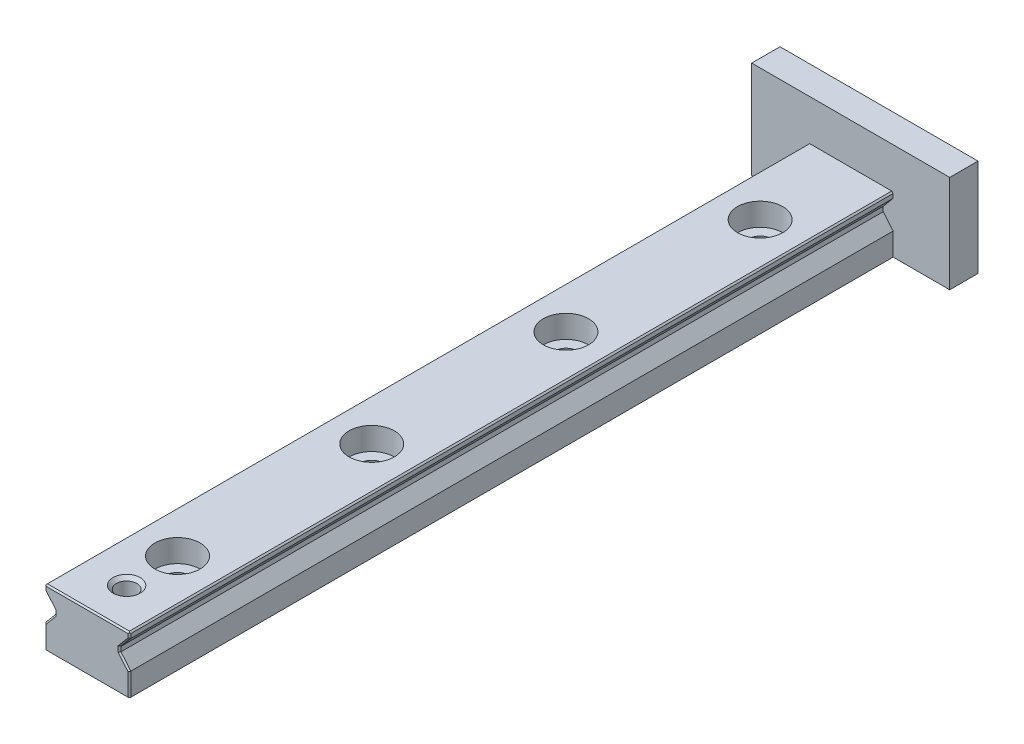
SolidWorks part; units mm, degrees
material "PET"
ref_plane "Přední rovina" through (0, 0, 0) normal (0, 0, 1) x (1, 0, 0)
ref_plane "Horní rovina" through (0, 0, 0) normal (0, 1, 0) x (1, 0, 0)
ref_plane "Pravá rovina" through (0, 0, 0) normal (1, 0, 0) x (0, 0, -1)
sketch "Skica1" plane through (0, 0, 0) normal (0, 0, 1) x (1, 0, 0)
  line L0 (0, 9) -> (1.7495, 6.915)
  line L1 (0, 0) -> (15, 0)
  line L2 (0, 0) -> (0, 4)
  line L3 (0, 10) -> (15, 10)
  line L4 (15, 0) -> (15, 4)
  line L5 (0, 0) -> (15, 10) construction
  line L6 (0, 10) -> (15, 0) construction
  line L7 (1.7495, 6.915) -> (1.7495, 6.085)
  line L8 (1.7495, 6.085) -> (0, 4)
  line L9 (0, 9) -> (0, 10)
  line L10 (7.5, 0) -> (7.5, 10) construction
  line L11 (15, 9) -> (13.2505, 6.915)
  line L12 (13.2505, 6.915) -> (13.2505, 6.085)
  line L13 (13.2505, 6.085) -> (15, 4)
  line L14 (15, 9) -> (15, 10)
  point P4 (7.5, 5)
  dimension "D1" = 10
  dimension "D2" = 15
  dimension "D3" = 4
  dimension "D4" = 5
  dimension "D5" = 0.83
  dimension "D6" = 50
  dimension "D7" = 50
extrude "Přidat vysunutím1" add sketch "Skica1" along normal blind 140
sketch "Skica2" plane through (0, 0, 0) normal (0, 0, -1) x (-1, 0, 0)
  line L1 (-25, 0) -> (10, 0)
  line L2 (-25, 0) -> (-25, 17.21)
  line L3 (-25, 17.21) -> (10, 17.21)
  line L4 (10, 0) -> (10, 17.21)
  line L5 (-25, 0) -> (10, 17.21) construction
  line L6 (-25, 17.21) -> (10, 0) construction
  line L7 (-15, 0) -> (-15, 4) construction
  line L8 (0, 4) -> (0, 0) construction
  point P4 (-7.5, 8.605)
  dimension "D1" = 17.21
  dimension "D2" = 10
  dimension "D3" = 10
extrude "Přidat vysunutím2" add sketch "Skica2" against normal blind 5
sketch "Skica3" plane through (0, 10, 0) normal (0, 1, 0) x (1, 0, 0)
  line L0 (7.5, -5) -> (7.5, -140) construction
  line L1 (15, -5) -> (0, -5) construction
  line L2 (15, -140) -> (0, -140) construction
  line L3 (-10, -5) -> (25, -5) construction
  circle A0 centre (7.5, -124) radius 2.1
  circle A4 centre (7.5, -89.6667) radius 2.1
  circle A5 centre (7.5, -55.3333) radius 2.1
  circle A6 centre (7.5, -21) radius 2.1
  dimension "D1" = 4.2
  dimension "D2" = 16
  dimension "D4" = 16
  dimension "D3" = 4
extrude "Odebrat vysunutím1" cut sketch "Skica3" against normal up to surface (10 mm away) up to face at (7.5, 0, 37.5)
sketch "Skica4" plane through (0, 10, 0) normal (0, 1, 0) x (1, 0, 0)
  circle A0 centre (7.5, -124) radius 4
  circle A3 centre (7.5, -89.67) radius 4
  circle A4 centre (7.5, -55.34) radius 4
  circle A5 centre (7.5, -21.01) radius 4
  dimension "D1" = 8
  dimension "D2" = 4
extrude "Odebrat vysunutím2" cut sketch "Skica4" against normal blind 4
sketch "Skica5" plane through (0, 10, 0) normal (0, 1, 0) x (1, 0, 0)
  line L0 (7.5, -124) -> (7.5, -140) construction
  line L1 (15, -140) -> (0, -140) construction
  circle A0 centre (7.5, -133) radius 1.8
  dimension "D1" = 3.6
  dimension "D2" = 7
extrude "Odebrat vysunutím3" cut sketch "Skica5" against normal up to surface (10 mm away) up to face at (7.5, 0, 126.1)
chamfer "Zkosení2" distance 0.25 angle 45 11 edges at (15, 9.5, 140) (14.1252, 7.9575, 140) (13.2505, 6.5, 140) (14.1252, 5.0425, 140) (15, 2, 140) (0, 2, 140) (0.8748, 5.0425, 140) (1.7495, 6.5, 140) (0.8748, 7.9575, 140) (0, 9.5, 140) (7.5, 10, 140)
chamfer "Zkosení3" distance 0.25 angle 45 2 edges at (15, 10, 72.375) (0, 10, 72.375)
chamfer "Zkosení4" distance 0.6 angle 45 1 edges at (5.7, 10, 133)
